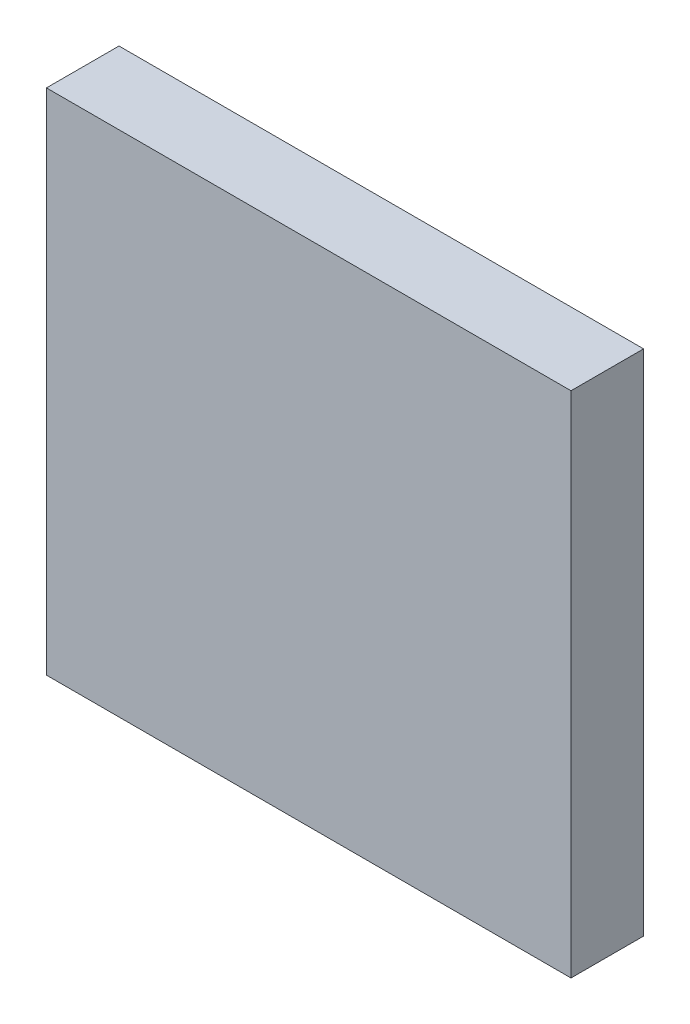
SolidWorks part; units mm, degrees
ref_plane "Front Plane" through (0, 0, 0) normal (0, 0, 1) x (1, 0, 0)
ref_plane "Top Plane" through (0, 0, 0) normal (0, 1, 0) x (1, 0, 0)
ref_plane "Right Plane" through (0, 0, 0) normal (1, 0, 0) x (0, 0, -1)
sketch "Sketch1" plane through (0, 0, 0) normal (0, 0, 1) x (1, 0, 0)
  line L1 (-47, 45.57) -> (47, 45.57)
  line L2 (-47, 45.57) -> (-47, -45.57)
  line L3 (-47, -45.57) -> (47, -45.57)
  line L4 (47, 45.57) -> (47, -45.57)
  line L5 (-47, 45.57) -> (47, -45.57) construction
  line L6 (-47, -45.57) -> (47, 45.57) construction
  point P0 (0, 0)
  dimension "D1" = 94
  dimension "D2" = 91.14
extrude "Boss-Extrude1" add sketch "Sketch1" along normal blind 13
